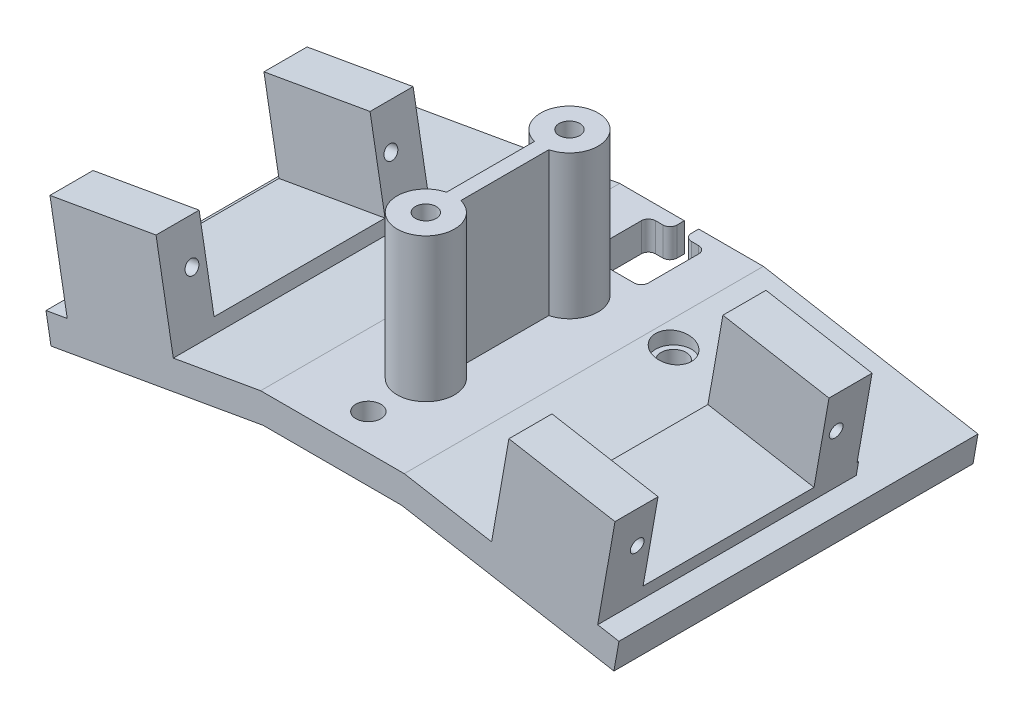
SolidWorks part; units mm, degrees
ref_plane "前视基准面" through (0, 0, 0) normal (0, 0, 1) x (1, 0, 0)
ref_plane "上视基准面" through (0, 0, 0) normal (0, 1, 0) x (1, 0, 0)
ref_plane "右视基准面" through (0, 0, 0) normal (1, 0, 0) x (0, 0, -1)
other "Configuration Table"
sketch "草图1" plane through (0, 0, 0) normal (0, 0, 1) x (1, 0, 0)
  line L0 (0, 0) -> (9.65, 0)
  line L1 (9.65, 0) -> (39.1943, -5.2094)
  line L2 (39.1943, -5.2094) -> (39.8889, -1.2702)
  line L3 (39.8889, -1.2702) -> (10, 4)
  line L4 (10, 4) -> (0, 4)
  line L5 (0, 4) -> (0, 0)
  dimension "D1" = 4
  dimension "D2" = 30
  dimension "D3" = 10
  dimension "D4" = 4
  dimension "D5" = 190
extrude "凸台-拉伸1" add sketch "草图1" along normal mid plane 50
sketch "草图2" plane through (0, 0, 25) normal (0, 0, 1) x (1, 0, 0)
  line L0 (22.1623, 1.8555) -> (22.4836, 3.6773)
  line L1 (39.8889, -1.2702) -> (10, 4) construction
  line L2 (22.4836, 3.6773) -> (37.2557, 1.0726)
  line L3 (37.2557, 1.0726) -> (36.9344, -0.7493)
  line L4 (36.9344, -0.7493) -> (22.1623, 1.8555)
  line L5 (39.1943, -5.2094) -> (39.8889, -1.2702) construction
  dimension "D1" = 1.85
  dimension "D2" = 18
  dimension "D3" = 15
extrude "凸台-拉伸2" add sketch "草图2" against normal blind 36
sketch "草图3" plane through (1.3068, 7.4114, 0) normal (0.1736, 0.9848, 0) x (0.9848, -0.1736, 0)
  line L0 (36.5034, 11) -> (36.5034, -25) construction
  line L1 (21.5034, -19) -> (36.5034, -19)
  line L2 (21.5034, -19) -> (21.5034, -25)
  line L3 (21.5034, -25) -> (36.5034, -25)
  line L4 (36.5034, -19) -> (36.5034, -25)
  line L5 (21.5034, 11) -> (21.5034, -25) construction
  line L6 (36.5034, 11) -> (36.5034, -25) construction
  line L7 (21.5034, 10.8) -> (36.5034, 10.8)
  line L8 (21.5034, 10.8) -> (21.5034, 4.8)
  line L9 (21.5034, 4.8) -> (36.5034, 4.8)
  line L10 (36.5034, 10.8) -> (36.5034, 4.8)
  line L11 (39.5034, -25) -> (36.5034, -25) construction
  dimension "D1" = 6
  dimension "D2" = 6
  dimension "D3" = 23.8
extrude "凸台-拉伸3" add sketch "草图3" along normal blind 12
sketch "草图4" plane through (35.9489, -6.3388, 0) normal (0.9848, -0.1736, 0) x (0, 0, -1)
  line L0 (4.8, 7.5257) -> (-19, 7.5257) construction
  line L1 (-19, 19.5257) -> (-19, 7.5257) construction
  line L2 (4.8, 19.5257) -> (4.8, 7.5257) construction
  circle A0 centre (-20.95, 14.0257) radius 0.95
  circle A1 centre (6.75, 14.0257) radius 0.95
  dimension "D1" = 6.5
  dimension "D2" = 6.5
  dimension "D3" = 1.95
  dimension "D4" = 1.95
  dimension "D5" = 1.9
  dimension "D6" = 1.9
extrude "切除-拉伸1" cut sketch "草图4" against normal blind 21
mirror "镜向1" about plane through (0, 0, 0) normal (1, 0, 0) of "切除-拉伸1", "凸台-拉伸3", "凸台-拉伸2", "凸台-拉伸1"
sketch "草图5" plane through (0, 4, 0) normal (0, 1, 0) x (1, 0, 0)
  circle A0 centre (0, -12) radius 4
  circle A1 centre (0, 8) radius 4
  circle A2 centre (0, 8) radius 1.45
  circle A3 centre (0, -12) radius 1.45
  dimension "D2" = 12
  dimension "D3" = 8
  dimension "D4" = 8
  dimension "D5" = 2.9
  dimension "D6" = 2.9
  dimension "D1" = 20
extrude "凸台-拉伸4" add sketch "草图5" along normal blind 20
sketch "草图6" plane through (0, 4, 0) normal (0, 1, 0) x (1, 0, 0)
  circle A0 centre (0, -20) radius 1.75
  circle A1 centre (-13, 9.5) radius 1.75
  circle A2 centre (13, 9.5) radius 1.75
  dimension "D1" = 20
  dimension "D2" = 26
  dimension "D3" = 29.5
  dimension "D4" = 3.5
  dimension "D5" = 13
extrude "切除-拉伸2" cut sketch "草图6" against normal blind 20
sketch "草图7" plane through (0, 4, 0) normal (0, 1, 0) x (1, 0, 0)
  circle A0 centre (-13, 9.5) radius 2.5
  circle A1 centre (13, 9.5) radius 2.5
  circle A2 centre (13, 9.5) radius 1.75 construction
  dimension "D1" = 5
extrude "切除-拉伸3" cut sketch "草图7" against normal blind 2
sketch "草图8" plane through (0, 4, 0) normal (0, 1, 0) x (1, 0, 0)
  line L0 (10, 25) -> (-10, 25) construction
  line L1 (-4, 23) -> (-1, 23)
  line L2 (-4, 23) -> (-4, 14)
  line L3 (-4, 14) -> (4, 14)
  line L4 (4, 23) -> (4, 14)
  line L5 (-4, 23) -> (4, 14) construction
  line L6 (-4, 14) -> (4, 23) construction
  line L7 (-1, 25) -> (1, 25)
  line L8 (-1, 25) -> (-1, 23)
  line L10 (1, 25) -> (1, 23)
  line L11 (1, 23) -> (4, 23)
  point P0 (0, 18.5)
  point P12 (0, 25)
  dimension "D1" = 8
  dimension "D2" = 9
  dimension "D3" = 14
  dimension "D4" = 2
extrude "切除-拉伸4" cut sketch "草图8" against normal through all
fillet "圆角4" radius 1 6 edges at (4, 2, -23) (-4, 2, -23) (1, 2, -23) (-1, 2, -23) (-4, 2, -14) (4, 2, -14)
sketch "草图9" plane through (0, 4, 0) normal (0, 1, 0) x (1, 0, 0)
  line L0 (0, 8) -> (0, -12.0981) construction
  line L1 (-1, 5) -> (1, 5)
  line L2 (-1, 5) -> (-1, -9)
  line L3 (-1, -9) -> (1, -9)
  line L4 (1, 5) -> (1, -9)
  line L5 (-1, 5) -> (1, -9) construction
  line L6 (-1, -9) -> (1, 5) construction
  line L7 (10, -25) -> (-10, -25) construction
  point P0 (0, -2)
  dimension "D1" = 2
  dimension "D2" = 16
  dimension "D3" = 14
extrude "凸台-拉伸5" add sketch "草图9" along normal up to surface (20 mm away) up to face at (-4, 24, 12)
